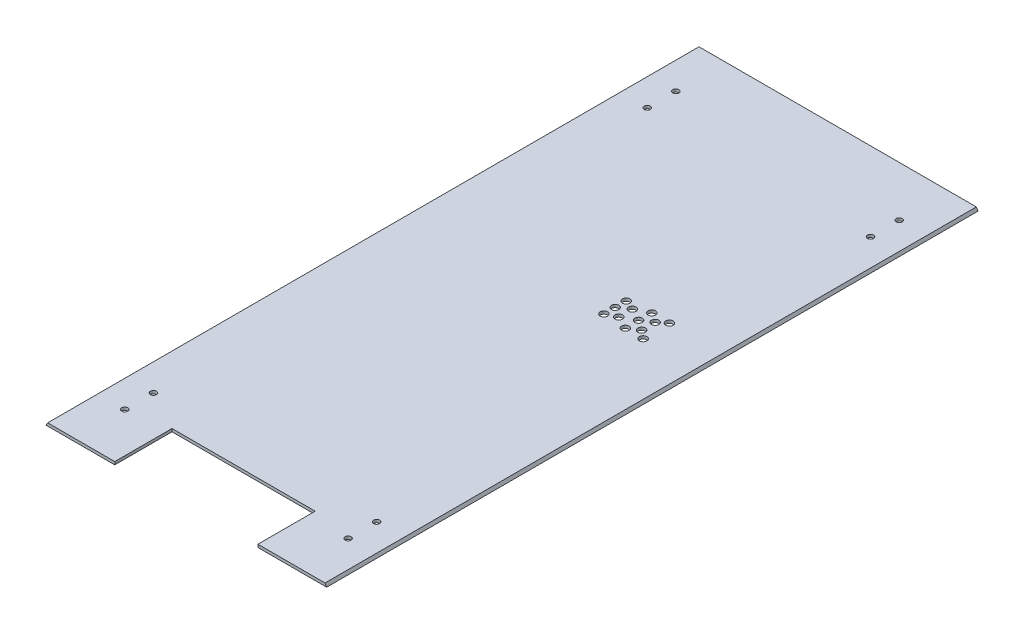
SolidWorks part; units mm, degrees
ref_plane "前视基准面" through (0, 0, 0) normal (0, 0, 1) x (1, 0, 0)
ref_plane "上视基准面" through (0, 0, 0) normal (0, 1, 0) x (1, 0, 0)
ref_plane "右视基准面" through (0, 0, 0) normal (1, 0, 0) x (0, 0, -1)
other "Configuration Table"
sketch "草图2" plane through (0, 0, 0) normal (0, 0, 1) x (1, 0, 0)
  line L0 (-98, -1) -> (-96.8453, 1)
  line L1 (-98, -1) -> (98.07, -1)
  line L3 (-96.8453, 1) -> (96.9153, 1)
  line L5 (-98, -1) -> (96.9217, 0.989) construction
  line L6 (-96.8525, 0.9876) -> (98.07, -1) construction
  line L7 (98.07, -1) -> (96.9153, 1)
  point P0 (0, 0)
  dimension "D1" = 60
  dimension "D2" = 196.07
  dimension "D3" = 60
  dimension "D4" = 2
  dimension "D5" = 1
extrude "凸台-拉伸1" add sketch "草图2" against normal blind 455
sketch "草图3" plane through (0, -1, 0) normal (0, -1, 0) x (-1, 0, 0)
  line L0 (98, 0) -> (-98.07, 0) construction
  line L1 (98, 455) -> (98, 0) construction
  line L2 (0, 0) -> (0, 458.5279) construction
  line L3 (98, 227.5) -> (-98.07, 227.5) construction
  line L4 (-98.07, 455) -> (-98.07, 0) construction
  circle A0 centre (78, 35) radius 2.1
  circle A1 centre (78, 55) radius 2.1
  circle A2 centre (-78, 55) radius 2.1
  circle A3 centre (-78, 35) radius 2.1
  circle A4 centre (-78, 420) radius 2.1
  circle A5 centre (-78, 400) radius 2.1
  circle A6 centre (78, 400) radius 2.1
  circle A7 centre (78, 420) radius 2.1
  dimension "D1" = 20
  dimension "D2" = 20
  dimension "D3" = 20
  dimension "D4" = 35
extrude "切除-拉伸1" cut sketch "草图3" against normal through all
sketch "草图4" plane through (0, -1, 0) normal (0, -1, 0) x (1, 0, 0)
  line L0 (98.07, -455) -> (98.07, 0) construction
  line L1 (-49.965, 0) -> (50.035, 0)
  line L2 (-49.965, 0) -> (-49.965, -40)
  line L3 (-49.965, -40) -> (50.035, -40)
  line L4 (50.035, 0) -> (50.035, -40)
  line L7 (-98, 0) -> (98.07, 0) construction
  dimension "D1" = 100
  dimension "D2" = 40
  dimension "D3" = 48.035
extrude "切除-拉伸2" cut sketch "草图4" against normal through all
sketch "草图5" plane through (0, -1, 0) normal (0, -1, 0) x (1, 0, 0)
  circle A0 centre (31.5601, -260.176) radius 2.6053
  circle A1 centre (31.5601, -268.0405) radius 2.6053
  circle A2 centre (31.5601, -275.7594) radius 2.6053
  circle A3 centre (38.5914, -263.5397) radius 2.6053
  circle A4 centre (38.5914, -273.0116) radius 2.6053
  circle A5 centre (47.5274, -268.4695) radius 2.6053
  circle A6 centre (54.5343, -263.5397) radius 2.6053
  circle A7 centre (54.5343, -273.0116) radius 2.6053
  circle A8 centre (47.6883, -277.5261) radius 2.6053
  circle A9 centre (47.6883, -259.0381) radius 2.6053
  circle A10 centre (60.3084, -258.8773) radius 2.6053
  circle A11 centre (59.9867, -277.5261) radius 2.6053
extrude "切除-拉伸3" cut sketch "草图5" against normal through all
